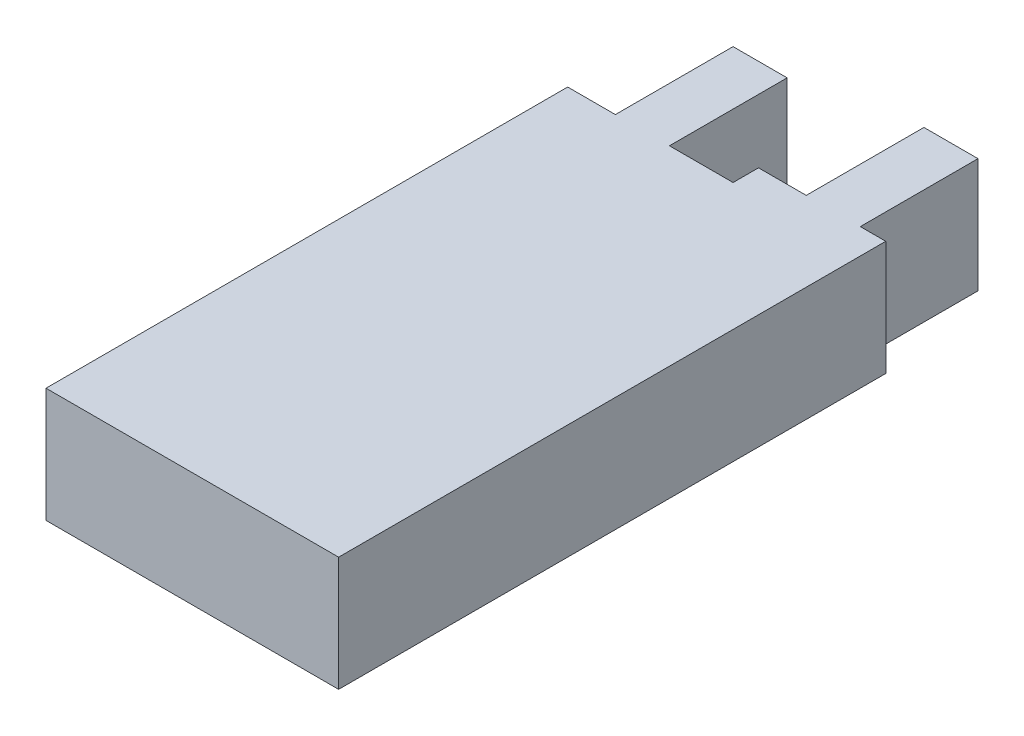
SolidWorks part; units mm, degrees
ref_plane "Front Plane" through (0, 0, 0) normal (0, 0, 1) x (1, 0, 0)
ref_plane "Top Plane" through (0, 0, 0) normal (0, 1, 0) x (1, 0, 0)
ref_plane "Right Plane" through (0, 0, 0) normal (1, 0, 0) x (0, 0, -1)
sketch "Sketch1" plane through (0, 0, 0) normal (0, 1, 0) x (1, 0, 0)
  line L0 (-23, 41) -> (-23, -41)
  line L1 (-23, -41) -> (23, -41)
  line L2 (23, -41) -> (23, 45)
  line L4 (0, 58.6863) -> (0, -55.685) construction
  line L6 (3, 41) -> (3, 45)
  line L7 (3, 45) -> (10.5, 45)
  line L8 (-15.5, 41) -> (-15.5, 59.5)
  line L9 (-15.5, 59.5) -> (-7, 59.5)
  line L10 (-7, 59.5) -> (-7, 41)
  line L11 (-23, 41) -> (-15.5, 41)
  line L12 (-7, 41) -> (3, 41)
  line L13 (10.5, 45) -> (10.5, 63.5)
  line L14 (10.5, 63.5) -> (19, 63.5)
  line L15 (19, 63.5) -> (19, 45)
  line L16 (19, 45) -> (23, 45)
  line L17 (-45.8737, 0) -> (49.7327, 0) construction
  dimension "D1" = 82
  dimension "D2" = 20
  dimension "D3" = 26
  dimension "D4" = 4
  dimension "D5" = 8.5
  dimension "D6" = 7.5
  dimension "D7" = 18.5
  dimension "D8" = 18.5
  dimension "D9" = 4
  dimension "D10" = 7.5
  dimension "D11" = 86
extrude "Boss-Extrude1" add sketch "Sketch1" along normal blind 18
